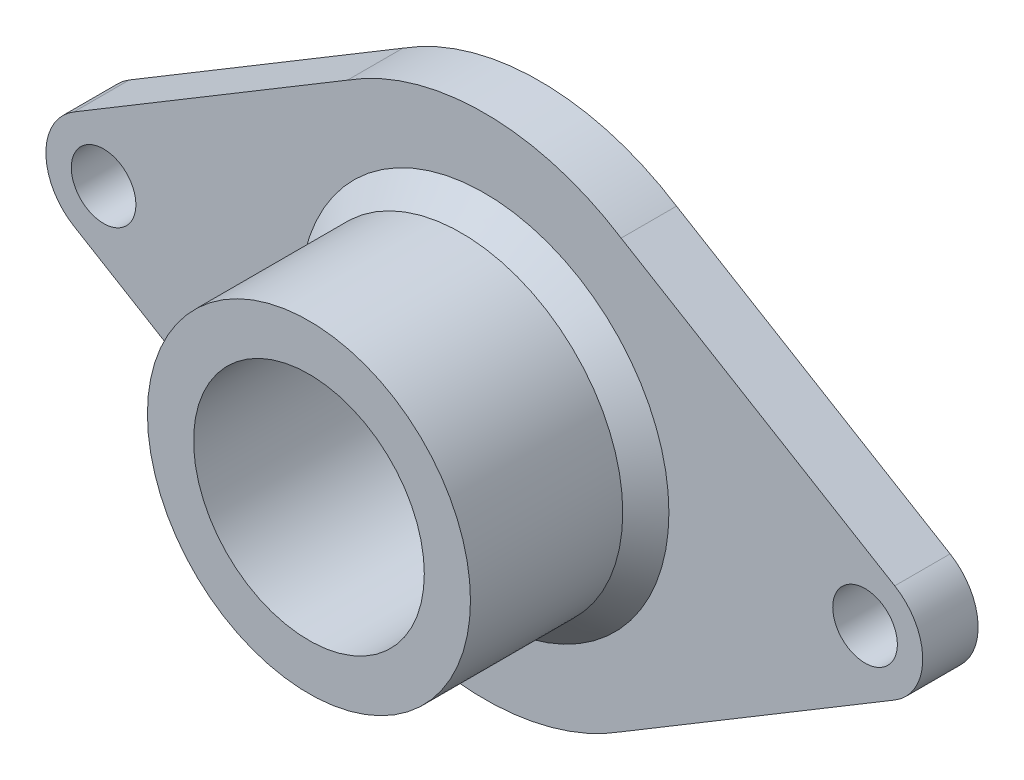
SolidWorks part; units mm, degrees
material "Gray Cast Iron (SN)"
ref_plane "Front Plane" through (0, 0, 0) normal (0, 0, 1) x (1, 0, 0)
ref_plane "Top Plane" through (0, 0, 0) normal (0, 1, 0) x (1, 0, 0)
ref_plane "Right Plane" through (0, 0, 0) normal (1, 0, 0) x (0, 0, -1)
sketch "Sketch1" plane through (0, 0, 0) normal (0, 0, 1) x (1, 0, 0)
  circle A0 centre (0, 0) radius 25
  circle A1 centre (0, 0) radius 35
  dimension "D1" = 70
  dimension "D2" = 50
extrude "Boss-Extrude1" add sketch "Sketch1" along normal blind 50
sketch "Sketch2" plane through (0, 0, 0) normal (0, 0, 1) x (1, 0, 0)
  line L2 (-29.6477, -46.3251) -> (-88.936, -10.7158)
  line L3 (-29.6477, 46.3251) -> (-88.936, 10.7158)
  line L4 (29.6477, -46.3251) -> (88.936, -10.7158)
  line L5 (29.6477, 46.3251) -> (88.936, 10.7158)
  arc A0 (29.6477, 46.3251) -> (-29.6477, 46.3251) centre (0, 0) ccw
  arc A1 (-29.6477, -46.3251) -> (29.6477, -46.3251) centre (0, 0) ccw
  arc A2 (-88.936, 10.7158) -> (-88.936, -10.7158) centre (-82.5, 0) ccw
  arc A3 (88.936, 10.7158) -> (88.936, -10.7158) centre (82.5, 0) cw
  circle A4 centre (0, 0) radius 35
  dimension "D1" = 110
  dimension "D4" = 25
  dimension "D2" = 70
extrude "Boss-Extrude2" add sketch "Sketch2" along normal blind 12
sketch "Sketch3" plane through (0, 0, 0) normal (0, 0, -1) x (-1, 0, 0)
  circle A0 centre (-82.5, 0) radius 7
  circle A1 centre (82.5, 0) radius 7
  dimension "D1" = 14
  dimension "D2" = 14
extrude "Cut-Extrude1" cut sketch "Sketch3" against normal blind 12
chamfer "Chamfer1" distance 5 angle 45 1 edges at (35, 0, 12)
